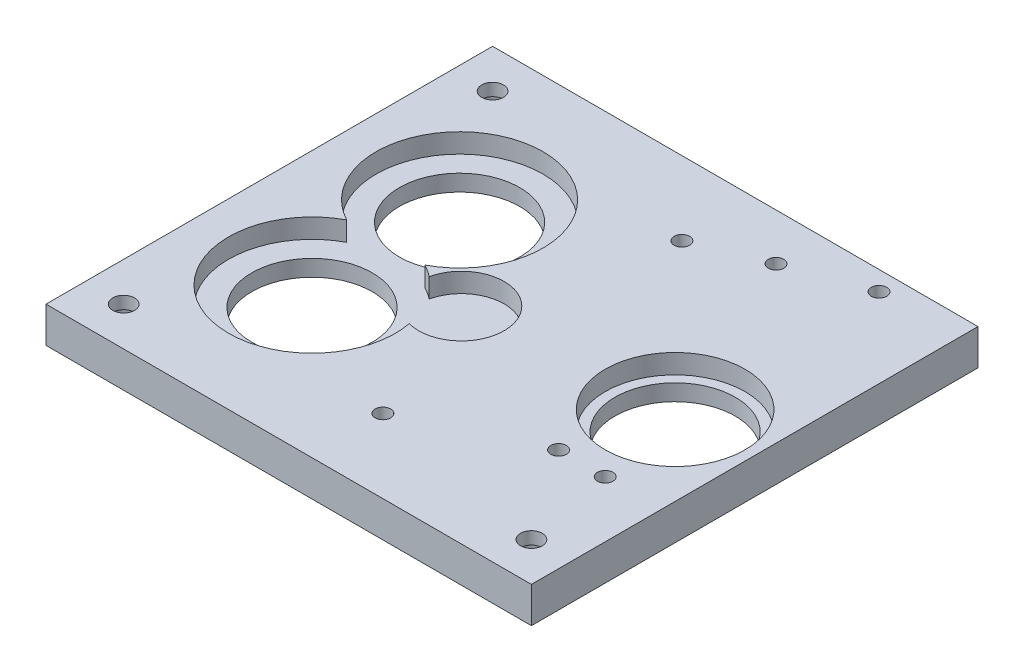
SolidWorks part; units mm, degrees
ref_plane "Front" through (0, 0, 0) normal (0, 0, 1) x (1, 0, 0)
ref_plane "Top" through (0, 0, 0) normal (0, 1, 0) x (1, 0, 0)
ref_plane "Right" through (0, 0, 0) normal (1, 0, 0) x (0, 0, -1)
sketch "Sketch1" plane through (0, 0, 0) normal (0, 1, 0) x (1, 0, 0)
  line L1 (-62.5, -57.5) -> (62.5, -57.5)
  line L2 (-62.5, -57.5) -> (-62.5, 57.5)
  line L3 (-62.5, 57.5) -> (62.5, 57.5)
  line L4 (62.5, -57.5) -> (62.5, 57.5)
  line L5 (-62.5, -57.5) -> (62.5, 57.5) construction
  line L6 (-62.5, 57.5) -> (62.5, -57.5) construction
  point P0 (0, 0)
  dimension "D1" = 125
  dimension "D2" = 115
extrude "Test_Base_Postion" add sketch "Sketch1" along normal blind 9.215
sketch "Fingers_Position" plane through (0, 9.215, 0) normal (0, 1, 0) x (1, 0, 0)
  line L0 (-62.5, 0) -> (62.5, 0) construction
  line L1 (-62.5, 57.5) -> (-62.5, -57.5) construction
  line L2 (62.5, -57.5) -> (62.5, 57.5) construction
  line L3 (-18.75, 35) -> (-18.75, 3) construction
  line L4 (-46.25, 35) -> (8.75, 35) construction
  line L5 (-46.25, 35) -> (-46.25, 3) construction
  line L6 (-46.25, 3) -> (8.75, 3) construction
  line L7 (8.75, 35) -> (8.75, 3) construction
  line L8 (8.75, -35) -> (-46.25, -35) construction
  line L9 (8.75, -35) -> (8.75, -3) construction
  line L10 (8.75, -3) -> (-46.25, -3) construction
  line L11 (-46.25, -35) -> (-46.25, -3) construction
  line L12 (-18.75, 19) -> (-46.25, 19) construction
  line L13 (-18.75, -3) -> (-18.75, -35) construction
  line L14 (-46.25, -19) -> (-18.75, -19) construction
  line L15 (-46.25, -19) -> (-52.5, -19) construction
  circle A0 centre (-32.5, -19) radius 20 construction
  circle A1 centre (-32.5, -19) radius 20.5 construction
  circle A2 centre (-32.5, 19) radius 20 construction
  circle A3 centre (-32.5, 19) radius 20.5 construction
  circle A4 centre (-32.5, 19) radius 19 construction
  circle A5 centre (-32.5, -19) radius 19 construction
  dimension "D1" = 40
  dimension "D2" = 41
  dimension "D8" = 38
  dimension "D3" = 55
  dimension "D4" = 32
  dimension "D5" = 55
  dimension "D6" = 32
  dimension "D7" = 10
sketch "Intermediate_Gear_Position" plane through (0, 9.215, 0) normal (0, 1, 0) x (1, 0, 0)
  line L0 (-51.25, 7.3419) -> (-27.25, 7.3419) construction
  line L1 (-27.25, -10.6581) -> (-51.25, -10.6581) construction
  line L2 (-27.25, -10.6581) -> (-27.25, 25.3419) construction
  line L3 (-27.25, 25.3419) -> (-51.25, 25.3419) construction
  line L4 (-51.25, -10.6581) -> (-51.25, 25.3419) construction
  line L5 (-39.25, 7.3419) -> (-39.25, -10.6581) construction
  line L6 (8.75, 35) -> (8.75, 3) construction
  circle A0 centre (-39.25, -1.6581) radius 14 construction
  circle A1 centre (-39.25, -1.6581) radius 13.5 construction
  circle A2 centre (-8.5769, -4.4507) radius 19 construction
  circle A3 centre (-8.5769, -4.4507) radius 18 construction
  circle A4 centre (-8.5769, -4.4507) radius 10 construction
  circle A5 centre (-8.5769, -4.4507) radius 10.5 construction
  circle A6 centre (-39.25, -1.6581) radius 12.8 construction
  circle A7 centre (-8.5769, -4.4507) radius 9 construction
  circle A8 centre (-32.5, -19) radius 19 construction
  point P22 (-10.5315, -1.6395)
  dimension "D3" = 28
  dimension "D4" = 27
  dimension "D5" = 38
  dimension "D6" = 36
  dimension "D7" = 21
  dimension "D8" = 20
  dimension "D10" = 18
  dimension "D11" = 25.6
  dimension "D1" = 24
  dimension "D2" = 36
  dimension "D9" = 36
  dimension "D12" = 33.5
sketch "Thumb_Position" plane through (0, 9.215, 0) normal (0, 1, 0) x (1, 0, 0)
  line L0 (42, 49) -> (42, -6) construction
  line L1 (58, -6) -> (26, -6) construction
  line L2 (58, -6) -> (58, 49) construction
  line L3 (58, 49) -> (26, 49) construction
  line L4 (26, -6) -> (26, 49) construction
  line L5 (30, -9) -> (54, -9) construction
  line L6 (54, -27) -> (30, -27) construction
  line L7 (54, -27) -> (54, 9) construction
  line L8 (54, 9) -> (30, 9) construction
  line L9 (30, -27) -> (30, 9) construction
  line L10 (42, 9) -> (42, -9) construction
  line L11 (62.5, -57.5) -> (62.5, 57.5) construction
  line L12 (-62.5, 0) -> (62.5, 0) construction
  circle A0 centre (42, 0) radius 17.75 construction
  circle A1 centre (42, 0) radius 9 construction
  dimension "D1" = 18
  dimension "D2" = 35.5
  dimension "D3" = 24
  dimension "D4" = 36
  dimension "D5" = 55
  dimension "D6" = 32
  dimension "D7" = 20.5
  dimension "D8" = 40
sketch "Sketch8" plane through (0, 9.215, 0) normal (0, 1, 0) x (1, 0, 0)
  circle A0 centre (-32.5, 19) radius 21.5
  circle A1 centre (-32.5, -19) radius 21.5
  dimension "D1" = 43
extrude "Finger_Gears" cut sketch "Sketch8" against normal blind 5 contours A1 A0 | A0 A1 | A0 A1
sketch "Sketch9" plane through (0, 9.215, 0) normal (0, 1, 0) x (1, 0, 0)
  circle A0 centre (-8.5769, -4.4507) radius 11
  dimension "D1" = 22
extrude "Intermediate_Gear" cut sketch "Sketch9" against normal blind 5
sketch "Sketch11" plane through (0, 9.215, 0) normal (0, 1, 0) x (1, 0, 0)
  circle A0 centre (42, 0) radius 18
  dimension "D1" = 36
extrude "XL320_Finger_Knuckle_Mount" cut sketch "Sketch11" against normal blind 5
sketch "Sketch10" plane through (0, 9.215, 0) normal (0, 1, 0) x (1, 0, 0)
  circle A0 centre (-32.5, 19) radius 15.5
  circle A1 centre (-32.5, -19) radius 15.5
  circle A2 centre (42, 0) radius 15.5
  dimension "D1" = 31
extrude "Connect_Finger_Holes" cut sketch "Sketch10" against normal through all
sketch "Thumb_Mount_Holes" plane through (0, 9.215, 0) normal (0, 1, 0) x (1, 0, 0)
  line L0 (42, 49) -> (42, 52.5) construction
  line L1 (58, 49) -> (26, 49) construction
  line L2 (26, 49) -> (22.5, 49) construction
  line L3 (22.5, 49) -> (22.5, 45.5) construction
  line L4 (42, -27) -> (42, -9) construction
  line L5 (54, -27) -> (30, -27) construction
  line L6 (48, -27) -> (48, -24) construction
  line L7 (48, -24) -> (54, -24) construction
  line L8 (54, -27) -> (54, 9) construction
  circle A0 centre (22.5, 45.5) radius 2
  circle A1 centre (42, 52.5) radius 2
  circle A2 centre (48, -24) radius 2
  circle A3 centre (36, -24) radius 2
  dimension "D3" = 4
  dimension "D5" = 4
  dimension "D1" = 6
  dimension "D2" = 3
  dimension "D4" = 3.5
extrude "Thumb_Mount_Holes_(M4)" cut sketch "Thumb_Mount_Holes" against normal through all
sketch "Sketch16" plane through (0, 9.215, 0) normal (0, 1, 0) x (1, 0, 0)
  line L0 (-62.5, 0) -> (62.5, 0) construction
  line L1 (-62.5, 57.5) -> (-62.5, -57.5) construction
  line L2 (8.75, 35) -> (8.75, 38.5) construction
  line L3 (8.75, 38.5) -> (5.25, 38.5) construction
  circle A0 centre (5.25, 38.5) radius 2
  circle A1 centre (5.25, -38.5) radius 2
  dimension "D2" = 4
  dimension "D1" = 3.5
extrude "Fingers_Mount_Holes_(M4)" cut sketch "Sketch16" against normal through all
sketch "Sketch17" plane through (0, 9.215, 0) normal (0, 1, 0) x (1, 0, 0)
  line L0 (-62.5, 47.5) -> (-52.5, 47.5) construction
  line L1 (-62.5, 57.5) -> (-62.5, -57.5) construction
  line L2 (62.5, 57.5) -> (-62.5, 57.5) construction
  line L3 (-62.5, 0) -> (62.5, 0) construction
  line L4 (0, 0) -> (0, -57.5) construction
  line L5 (-62.5, -57.5) -> (62.5, -57.5) construction
  circle A0 centre (-52.5, 47.5) radius 2.8
  circle A1 centre (-52.5, -47.5) radius 2.8
  circle A2 centre (52.5, -47.5) radius 2.8
  dimension "D3" = 5.6
  dimension "D1" = 10
  dimension "D2" = 10
extrude "Connect_Holes_(M6)" cut sketch "Sketch17" against normal through all
sketch "Sketch18" plane through (0, 0, 0) normal (0, -1, 0) x (1, 0, 0)
  circle A0 centre (5.25, 38.5) radius 3.75
  circle A1 centre (5.25, -38.5) radius 3.75
  circle A2 centre (22.5, -45.5) radius 3.75
  circle A3 centre (42, -52.5) radius 3.75
  circle A4 centre (36, 24) radius 3.75
  circle A5 centre (48, 24) radius 3.75
  dimension "D1" = 7.5
extrude "Nuts_(M4)" cut sketch "Sketch18" against normal blind 4
sketch "Sketch19" plane through (0, 0, 0) normal (0, -1, 0) x (1, 0, 0)
  circle A0 centre (-52.5, 47.5) radius 5.25
  circle A1 centre (52.5, 47.5) radius 5.25
  circle A2 centre (-52.5, -47.5) radius 5.25
  dimension "D1" = 10.5
extrude "Cut-Extrude5" cut sketch "Sketch19" against normal blind 6
